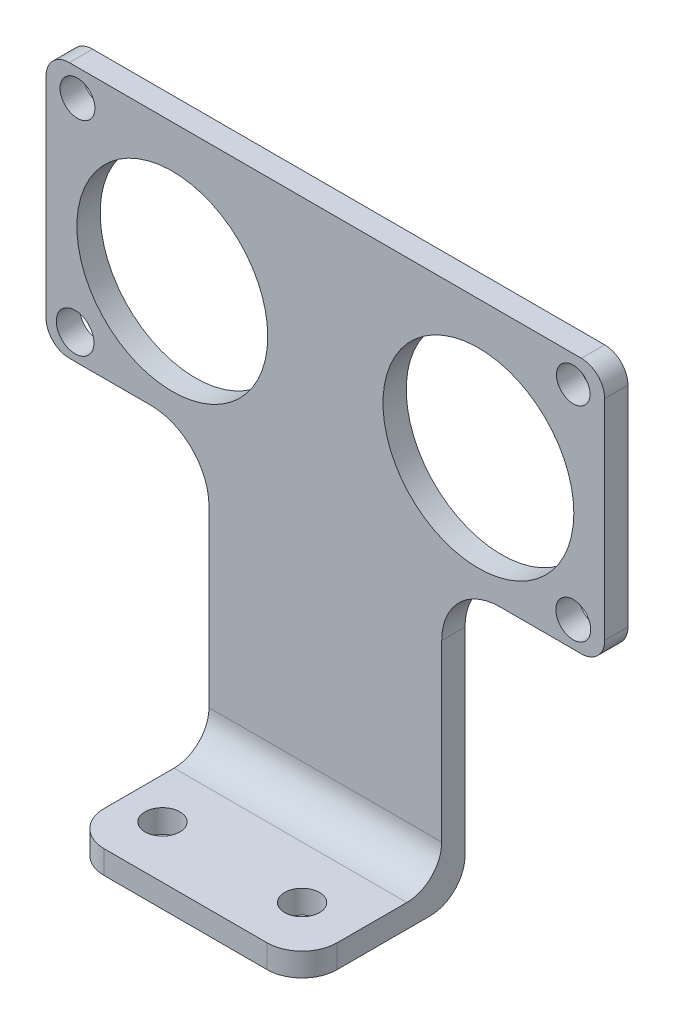
SolidWorks part; units mm, degrees
ref_plane "Front Plane" through (0, 0, 0) normal (0, 0, 1) x (1, 0, 0)
ref_plane "Top Plane" through (0, 0, 0) normal (0, 1, 0) x (1, 0, 0)
ref_plane "Right Plane" through (0, 0, 0) normal (1, 0, 0) x (0, 0, -1)
sketch "Sketch1" plane through (0, 0, 0) normal (0, 0, 1) x (1, 0, 0)
  line L1 (-19.7792, 13.552) -> (24.2208, 13.552)
  line L2 (-21.7792, 11.552) -> (-21.7792, -6.448)
  line L3 (-19.7792, -8.448) -> (-12.7792, -8.448)
  line L4 (26.2208, 11.552) -> (26.2208, -6.448)
  line L6 (-7.7792, -13.448) -> (-7.7792, -33.448)
  line L7 (-7.7792, -33.448) -> (12.2208, -33.448)
  line L8 (12.2208, -13.448) -> (12.2208, -33.448)
  line L9 (24.2208, -8.448) -> (17.2208, -8.448)
  arc A0 (24.2208, -8.448) -> (26.2208, -6.448) centre (24.2208, -6.448) ccw
  arc A1 (24.2208, 13.552) -> (26.2208, 11.552) centre (24.2208, 11.552) cw
  arc A2 (-21.7792, -6.448) -> (-19.7792, -8.448) centre (-19.7792, -6.448) ccw
  arc A3 (-19.7792, 13.552) -> (-21.7792, 11.552) centre (-19.7792, 11.552) ccw
  arc A4 (-7.7792, -13.448) -> (-12.7792, -8.448) centre (-12.7792, -13.448) ccw
  arc A6 (12.2208, -13.448) -> (17.2208, -8.448) centre (17.2208, -13.448) cw
  dimension "D3" = 2
  dimension "D7" = 5
  dimension "D2" = 5
  dimension "D1" = 48
  dimension "D4" = 20
  dimension "D5" = 14
  dimension "D6" = 25
extrude "Boss-Extrude1" add sketch "Sketch1" along normal blind 2
sketch "Sketch3" plane through (0, 0, 2) normal (0, 0, 1) x (1, 0, 0)
  line L0 (-19.7792, -8.448) -> (-12.7792, -8.448) construction
  line L1 (-21.7792, 11.552) -> (-21.7792, -6.448) construction
  circle A0 centre (-10.9292, 1.702) radius 8.2
  circle A1 centre (15.3708, 1.702) radius 8.2
  dimension "D1" = 10.15
  dimension "D3" = 26.3
  dimension "D4" = 16.4
  dimension "D5" = 16.4
  dimension "D2" = 10.85
extrude "Cut-Extrude2" cut sketch "Sketch3" against normal through all
sketch "Sketch4" plane through (0, 0, 2) normal (0, 0, 1) x (1, 0, 0)
  line L0 (-21.7792, 11.552) -> (-21.7792, -6.448) construction
  line L1 (24.2208, 13.552) -> (-19.7792, 13.552) construction
  line L2 (-19.7792, -8.448) -> (-12.7792, -8.448) construction
  line L3 (26.2208, -6.448) -> (26.2208, 11.552) construction
  line L4 (17.2208, -8.448) -> (24.2208, -8.448) construction
  circle A0 centre (-19.0792, 11.252) radius 1.5
  circle A1 centre (-19.2792, -6.248) radius 1.6187
  circle A2 centre (23.5208, 11.252) radius 1.4413
  circle A3 centre (23.5208, -6.248) radius 1.5
  dimension "D1" = 2.7
  dimension "D4" = 2.5
  dimension "D7" = 2.2
  dimension "D2" = 2.3
  dimension "D3" = 2.2
  dimension "D5" = 2.7
  dimension "D6" = 2.3
extrude "Cut-Extrude3" cut sketch "Sketch4" against normal through all
sketch "Sketch6" plane through (0, 0, 2) normal (0, 0, 1) x (1, 0, 0)
  line L0 (-7.7792, -13.448) -> (-7.7792, -33.448) construction
  line L1 (-7.7792, -31.448) -> (12.2208, -31.448)
  line L2 (-7.7792, -31.448) -> (-7.7792, -33.448)
  line L3 (-7.7792, -33.448) -> (12.2208, -33.448)
  line L4 (12.2208, -31.448) -> (12.2208, -33.448)
  dimension "D1" = 2
extrude "Boss-Extrude2" add sketch "Sketch6" along normal blind 12
fillet "Fillet1" radius 3 1 edges at (2.2208, -33.448, 0)
fillet "Fillet2" radius 3 1 edges at (2.2208, -31.448, 2)
sketch "Sketch7" plane through (0, -31.448, 0) normal (0, 1, 0) x (1, 0, 0)
  line L0 (-7.7792, -14) -> (-7.7792, -5) construction
  line L1 (12.2208, -5) -> (-7.7792, -5) construction
  circle A0 centre (-4.2792, -9.5) radius 1.5
  circle A1 centre (7.7208, -9.5) radius 1.5
  dimension "D1" = 3
  dimension "D2" = 3
  dimension "D4" = 3.5
  dimension "D3" = 4.5
  dimension "D6" = 12
extrude "Cut-Extrude4" cut sketch "Sketch7" against normal through all
fillet "Fillet3" radius 3 2 edges at (12.2208, -32.448, 14) (-7.7792, -32.448, 14)
